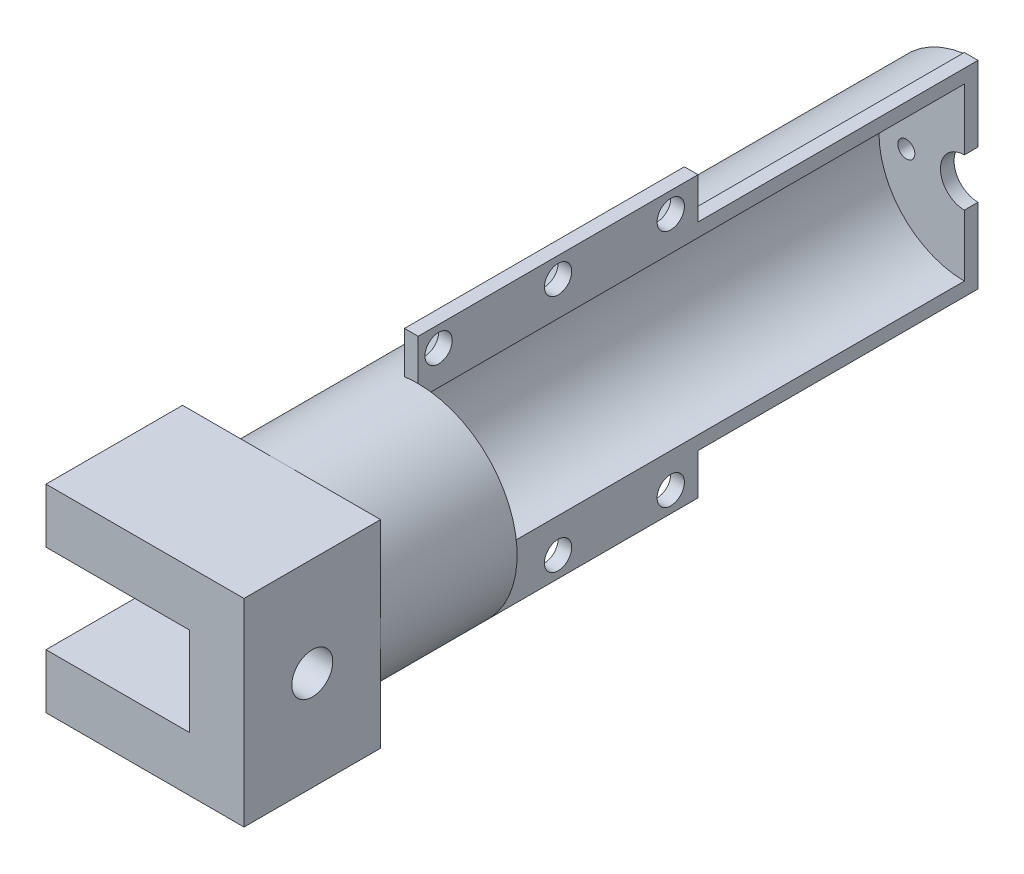
SolidWorks part; units mm, degrees
material "ABS PC"
ref_plane "Front Plane" through (0, 0, 0) normal (0, 0, 1) x (1, 0, 0)
ref_plane "Top Plane" through (0, 0, 0) normal (0, 1, 0) x (1, 0, 0)
ref_plane "Right Plane" through (0, 0, 0) normal (1, 0, 0) x (0, 0, -1)
sketch "Sketch1" plane through (0, 0, 0) normal (0, 0, 1) x (1, 0, 0)
  circle A0 centre (0, 0) radius 14.5
  dimension "D1" = 29
extrude "Boss-Extrude1" add sketch "Sketch1" along normal blind 120
sketch "Sketch2" plane through (0, 0, 0) normal (0, 0, -1) x (-1, 0, 0)
  circle A0 centre (0, 0) radius 12
  dimension "D1" = 24
extrude "Cut-Extrude1" cut sketch "Sketch2" against normal up to next
sketch "Sketch3" plane through (0, 0, 0) normal (0, 0, -1) x (-1, 0, 0)
  circle A0 centre (0, 0) radius 12.5
  dimension "D1" = 25
extrude "Cut-Extrude2" cut sketch "Sketch3" against normal blind 80
sketch "Sketch4" plane through (0, 0, 0) normal (0, 0, -1) x (-1, 0, 0)
  line L0 (0, -14.5) -> (0, 14.5)
  circle A0 centre (0, 0) radius 14.5 construction
  arc A1 (0, 14.5) -> (0, -14.5) centre (0, 0) ccw
extrude "Cut-Extrude3" cut sketch "Sketch4" against normal blind 80
sketch "Sketch5" plane through (0, 0, 0) normal (0, 0, -1) x (-1, 0, 0)
  line L0 (0, -14.5) -> (0, 14.5)
  arc A0 (0, -14.5) -> (0, 14.5) centre (0, 0) ccw
extrude "Boss-Extrude2" add sketch "Sketch5" along normal blind 2
sketch "Sketch6" plane through (0, 0, -2) normal (0, 0, -1) x (-1, 0, 0)
  line L0 (0, -3.5) -> (0, 3.5)
  arc A0 (0, -3.5) -> (0, 3.5) centre (0, 0) ccw
  dimension "D1" = 7
extrude "Cut-Extrude4" cut sketch "Sketch6" against normal up to next
sketch "Sketch7" plane through (0, 0, -2) normal (0, 0, -1) x (-1, 0, 0)
  circle A0 centre (8.5, 0) radius 1.25
  dimension "D1" = 2.5
  dimension "D2" = 8.5
extrude "Cut-Extrude5" cut sketch "Sketch7" against normal up to next
sketch "Sketch8" plane through (0, 0, -2) normal (0, 0, -1) x (-1, 0, 0)
  line L0 (0, -14.5) -> (0, -20.5)
  line L1 (0, -20.5) -> (2, -20.5)
  line L2 (2, -20.5) -> (2, -14.3614)
  arc A0 (0, -14.5) -> (0, 14.5) centre (0, 0) ccw construction
  arc A2 (0, -14.5) -> (2, -14.3614) centre (0, 0) ccw
  dimension "D1" = 6
  dimension "D2" = 2
extrude "Boss-Extrude3" add sketch "Sketch8" against normal blind 82
sketch "Sketch9" plane through (0, 0, 0) normal (1, 0, 0) x (0, 0, -1)
  line L0 (-80, -12.5) -> (0, -12.5) construction
  line L1 (2, -20.5) -> (-39, -20.5)
  line L2 (2, -20.5) -> (2, -14.5)
  line L3 (2, -14.5) -> (-39, -14.5)
  line L4 (-39, -20.5) -> (-39, -14.5)
  dimension "D1" = 2
  dimension "D2" = 41
extrude "Cut-Extrude6" cut sketch "Sketch9" against normal up to next
sketch "Sketch10" plane through (0, 0, 0) normal (1, 0, 0) x (0, 0, -1)
  line L0 (-80, -20.5) -> (-39, -20.5) construction
  line L1 (-80, -14.5) -> (-80, -20.5) construction
  line L2 (-39, -14.5) -> (-39, -20.5) construction
  circle A0 centre (-77, -17.5) radius 2
  circle A1 centre (-59.5, -17.5) radius 2
  circle A2 centre (-43, -17.5) radius 2
  point P10 (-80, -17.5)
  dimension "D3" = 4
  dimension "D4" = 4
  dimension "D9" = 4
  dimension "D1" = 3
  dimension "D2" = 3
  dimension "D5" = 20.5
  dimension "D6" = 3
  dimension "D7" = 3
  dimension "D8" = 4
extrude "Cut-Extrude7" cut sketch "Sketch10" against normal up to next
mirror "Mirror1" about plane through (0, 0, 0) normal (0, 1, 0) of "Cut-Extrude6", "Boss-Extrude3", "Cut-Extrude7"
sketch "Sketch11" [suppressed] plane through (0, 0, 200) normal (0, 0, 1) x (1, 0, 0)
  circle A0 centre (0, 0) radius 14.5
extrude "Cut-Extrude8" [suppressed] cut sketch "Sketch11" against normal blind 120
sketch "Sketch12" plane through (0, 0, 120) normal (0, 0, 1) x (1, 0, 0)
  line L1 (-14.5, 14.5) -> (14.5, 14.5)
  line L2 (-14.5, 14.5) -> (-14.5, -14.5)
  line L3 (-14.5, -14.5) -> (14.5, -14.5)
  line L4 (14.5, 14.5) -> (14.5, -14.5)
  line L5 (-14.5, 14.5) -> (14.5, -14.5) construction
  line L6 (-14.5, -14.5) -> (14.5, 14.5) construction
  circle A0 centre (0, 0) radius 14.5 construction
  point P0 (0, 0)
  dimension "D1" = 14.5
  dimension "D2" = 14.5
extrude "Boss-Extrude4" add sketch "Sketch12" against normal blind 20
sketch "Sketch13" plane through (0, 0, 120) normal (0, 0, 1) x (1, 0, 0)
  line L0 (14.5, -14.5) -> (14.5, 14.5) construction
  line L1 (-6.5, 6.5) -> (6.5, 6.5)
  line L2 (-6.5, 6.5) -> (-6.5, -6.5)
  line L3 (-6.5, -6.5) -> (6.5, -6.5)
  line L4 (6.5, 6.5) -> (6.5, -6.5)
  line L5 (-6.5, 6.5) -> (6.5, -6.5) construction
  line L6 (-6.5, -6.5) -> (6.5, 6.5) construction
  line L7 (-14.5, -14.5) -> (14.5, -14.5) construction
  point P0 (0, 0)
  dimension "D1" = 8
  dimension "D2" = 8
extrude "Cut-Extrude9" cut sketch "Sketch13" against normal up to next
sketch "Sketch14" plane through (-14.5, 0, 0) normal (-1, 0, 0) x (0, 0, 1)
  line L0 (100, 14.5) -> (100, 0) construction
  line L1 (120, -6.5) -> (100, -6.5)
  line L2 (120, -6.5) -> (120, 6.5)
  line L3 (120, 6.5) -> (100, 6.5)
  line L4 (100, -6.5) -> (100, 6.5)
  line L5 (100, 14.5) -> (120, 14.5) construction
  dimension "D1" = 8
extrude "Cut-Extrude10" cut sketch "Sketch14" against normal up to next
sketch "Sketch15" plane through (14.5, 0, 0) normal (1, 0, 0) x (0, 0, -1)
  line L0 (-100, -14.5) -> (-120, -14.5) construction
  line L1 (-100, -14.5) -> (-100, 0) construction
  circle A0 centre (-110, 0) radius 3
  dimension "D1" = 6
  dimension "D2" = 14.5
  dimension "D3" = 10
extrude "Cut-Extrude11" cut sketch "Sketch15" against normal up to next
